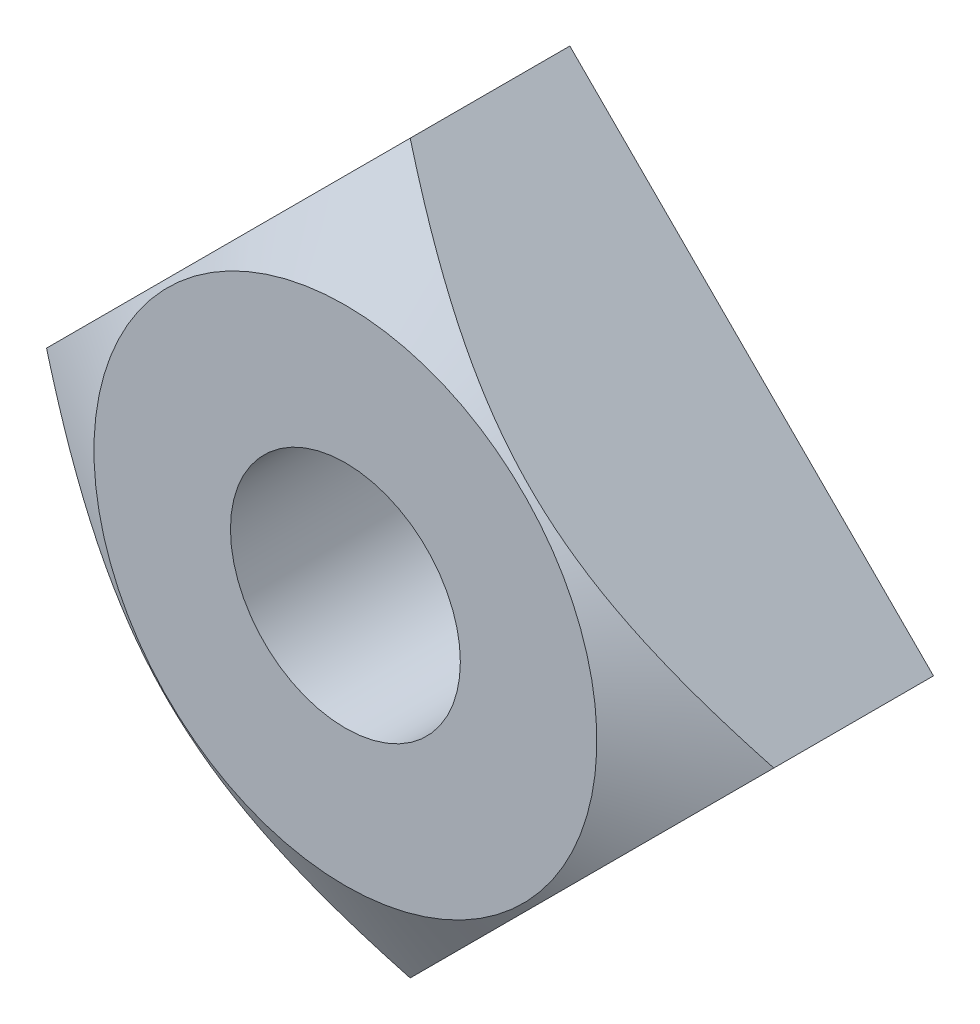
SolidWorks part; units mm, degrees
ref_plane "前视基准面" through (0, 0, 0) normal (0, 0, 1) x (1, 0, 0)
ref_plane "上视基准面" through (0, 0, 0) normal (0, 1, 0) x (1, 0, 0)
ref_plane "右视基准面" through (0, 0, 0) normal (1, 0, 0) x (0, 0, -1)
sketch "草图4" plane through (0, 0, 0) normal (0, 0, 1) x (1, 0, 0)
  line L0 (-3.8891, 0) -> (3.8891, 0) construction
  line L1 (0, 3.8891) -> (0, -3.8891) construction
  line L6 (3.8891, 0) -> (0, 3.8891)
  line L7 (-3.8891, 0) -> (0, 3.8891)
  line L10 (3.8891, 0) -> (0, -3.8891)
  line L11 (-3.8891, 0) -> (0, -3.8891)
  circle A0 centre (0, 0) radius 1.5 construction
  circle A1 centre (0, 0) radius 1.2294
  dimension "D1" = 90
  dimension "D" = 3
  dimension "D3" = 2.4588
  dimension "s(max)" = 5.5
sketch "草图5" plane through (0, 0, 0) normal (1, 0, 0) x (0, 0, -1)
  line L0 (0.6928, -3.8891) -> (0, -2.6891)
  line L1 (0, 2.6891) -> (0, -2.6891)
  line L2 (0.6928, 3.8891) -> (2.4, 3.8891)
  line L3 (2.4, 3.8891) -> (2.4, -3.8891)
  line L4 (0.6928, -3.8891) -> (2.4, -3.8891)
  line L5 (0, 1.5) -> (2.4, 1.5)
  line L6 (0, 1.2294) -> (2.4, 1.2294)
  line L7 (0.6928, 3.8891) -> (0, 2.6891)
  line L8 (0, 0) -> (2.4, 0) construction
  line L9 (0, 0) -> (0, 3.8891) construction
  line L10 (0, 1.5) -> (-0.1562, 1.2294)
  line L11 (0, 1.5) -> (0.1562, 1.2294)
  line L12 (0.1562, 1.2294) -> (-0.1562, 1.2294)
  line L13 (0, 0) -> (0, 3.8891)
  line L16 (-0.939, -3.8891) -> (-0.939, 2.8709) construction
  point P12 (1.1928, 3.8891)
  dimension "D1" = 3.339
  dimension "m(min)" = 2.4
  dimension "D2" = 30
  dimension "D3" = 3
  dimension "D4" = 2.4588
  dimension "D5" = 60
  dimension "D6" = 60
  dimension "D7" = 1.2
  dimension "e(min)" = 6.76
  dimension "P" = 0.5
sketch "草图7" plane through (0, 0, 0) normal (0, 0, 1) x (1, 0, 0)
  line L4 (-3.8891, 0) -> (0, 3.8891) construction
  line L7 (3.8891, 0) -> (0, 3.8891) construction
  line L8 (-3.8891, 0) -> (0, 3.8891)
  line L9 (-3.8891, 0) -> (0, -3.8891) construction
  line L10 (3.8891, 0) -> (0, -3.8891) construction
  line L11 (3.8891, 0) -> (0, 3.8891)
  line L12 (-3.8891, 0) -> (0, -3.8891)
  line L13 (3.8891, 0) -> (0, -3.8891)
  circle A1 centre (0, 0) radius 1.2294 construction
  circle A2 centre (0, 0) radius 1.2294
extrude "凸台-拉伸1" add sketch "草图7" against normal up to vertex (2.4 mm away) up to point (0, 3.8891, -2.4)
cosmetic thread "装饰螺纹线1" parameters "D2"=3
sketch "草图8" plane through (0, 0, 0) normal (1, 0, 0) x (0, 0, -1)
  line L9 (0.6928, 3.8891) -> (0, 2.6891) construction
  line L10 (0, 3.8891) -> (0, -3.8891) construction
  line L11 (2.4, 3.8891) -> (0, 3.8891) construction
  line L13 (0.6928, 3.8891) -> (0, 2.6891)
  line L14 (0, 3.8891) -> (0, 2.6891)
  line L15 (0.6928, 3.8891) -> (0, 3.8891)
  line L16 (0, 0) -> (2.4, 0) construction
revolve "切除-旋转1" cut sketch "草图8" angle 360 about L16
